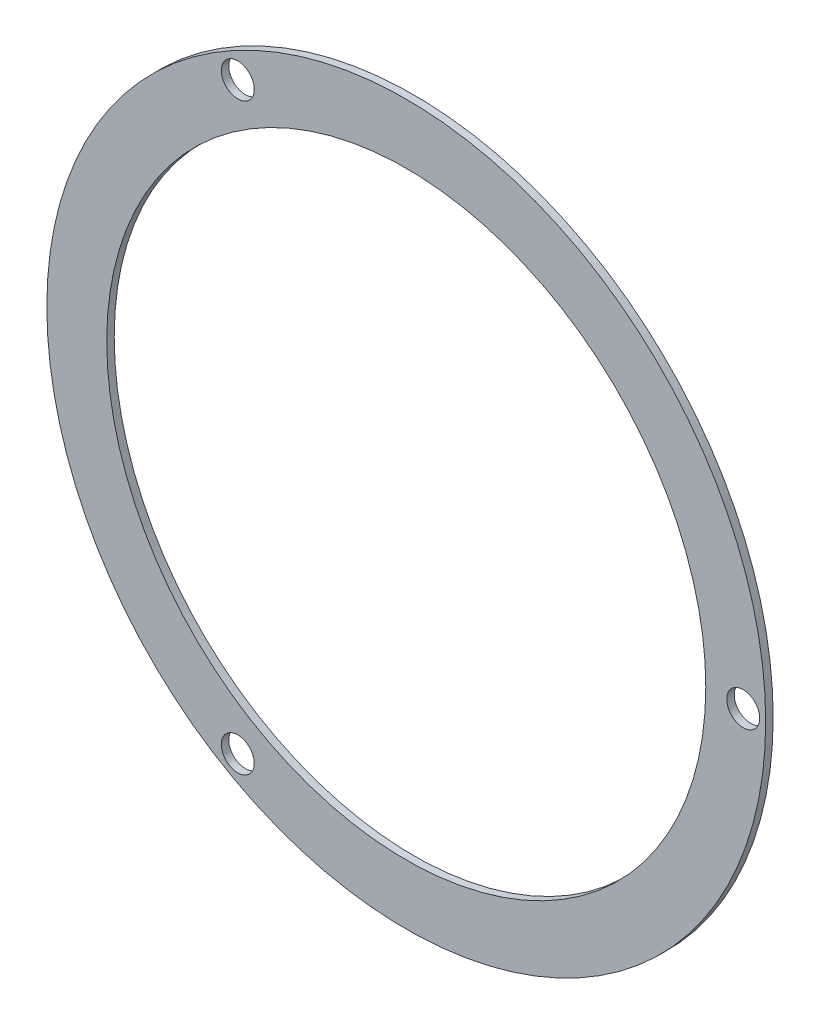
SolidWorks part; units mm, degrees
ref_plane "Front Plane" through (0, 0, 0) normal (0, 0, 1) x (1, 0, 0)
ref_plane "Top Plane" through (0, 0, 0) normal (0, 1, 0) x (1, 0, 0)
ref_plane "Right Plane" through (0, 0, 0) normal (1, 0, 0) x (0, 0, -1)
sketch "Sketch1" plane through (0, 0, 0) normal (0, 0, 1) x (1, 0, 0)
  circle A0 centre (0, 0) radius 20
  circle A1 centre (0, 0) radius 24
extrude "Boss-Extrude1" add sketch "Sketch1" along normal blind 0.5
sketch "Sketch2" plane through (0, 0, 0) normal (0, 0, -1) x (-1, 0, 0)
  circle A0 centre (-22.5, 0) radius 1.1
  circle A1 centre (11.25, 19.4856) radius 1.1
  circle A2 centre (11.25, -19.4856) radius 1.1
extrude "Retainer_Three_D2p2" cut sketch "Sketch2" against normal blind 0.51
